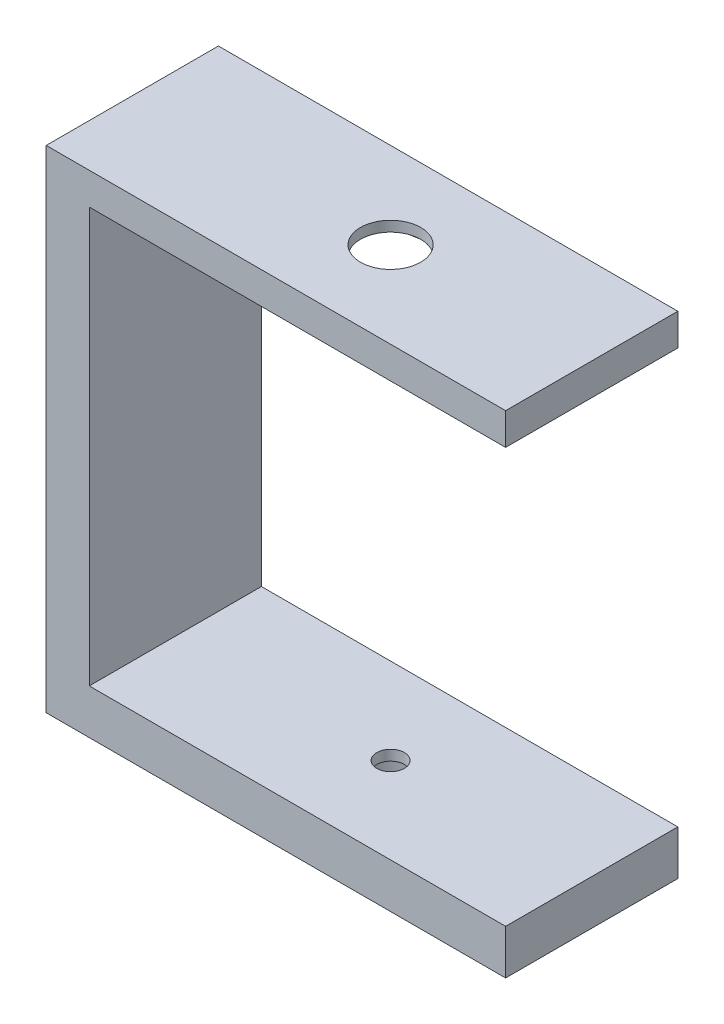
SolidWorks part; units mm, degrees
ref_plane "Alzado" through (0, 0, 0) normal (0, 0, 1) x (1, 0, 0)
ref_plane "Planta" through (0, 0, 0) normal (0, 1, 0) x (1, 0, 0)
ref_plane "Vista lateral" through (0, 0, 0) normal (1, 0, 0) x (0, 0, -1)
sketch "Croquis1" plane through (0, 0, 0) normal (0, 1, 0) x (1, 0, 0)
  line L1 (0, 0) -> (53.36, 0)
  line L2 (0, 0) -> (0, 20)
  line L3 (0, 20) -> (53.36, 20)
  line L4 (53.36, 0) -> (53.36, 20)
  dimension "D1" = 20
  dimension "D2" = 53.36
extrude "Saliente-Extruir1" add sketch "Croquis1" along normal blind 3.7
sketch "Croquis2" plane through (0, 0, 0) normal (0, -1, 0) x (1, 0, 0)
  line L0 (0, -20) -> (0, 0) construction
  line L1 (0, -20) -> (0, 0)
  line L2 (0, 0) -> (5, 0)
  line L3 (0, 0) -> (53.36, 0) construction
  line L4 (5, 0) -> (5, -20)
  line L5 (53.36, -20) -> (0, -20) construction
  line L6 (5, -20) -> (0, -20)
  dimension "D1" = 5
extrude "Saliente-Extruir2" add sketch "Croquis2" along normal blind 48.17
sketch "Croquis3" plane through (0, -48.17, 0) normal (0, -1, 0) x (1, 0, 0)
  line L0 (0, 0) -> (0, -20) construction
  line L1 (0, 0) -> (0, -20)
  line L2 (0, 0) -> (53.36, 0)
  line L3 (53.36, 0) -> (53.36, -20)
  line L4 (53.36, -20) -> (0, -20)
extrude "Saliente-Extruir3" add sketch "Croquis3" along normal blind 5.2
sketch "Croquis4" plane through (0, 0, 0) normal (0, -1, 0) x (1, 0, 0)
  line L0 (5, -10) -> (30, -10) construction
  line L1 (5, -20) -> (5, 0) construction
  line L2 (28.8973, -3.7465) -> (13.8394, -6.4016)
  line L3 (28.8973, -16.2535) -> (13.8394, -13.5984)
  line L4 (30, -3.65) -> (30, -16.35)
  arc A0 (28.8973, -16.2535) -> (30, -16.35) centre (30, -10) ccw
  arc A1 (13.8394, -13.5984) -> (13.8394, -6.4016) centre (14.4739, -10) cw
  arc A2 (30, -3.65) -> (28.8973, -3.7465) centre (30, -10) ccw
  point P10 (10.82, -10)
  dimension "D1" = 12.7
  dimension "D2" = 25
  dimension "D3" = 19.18
  dimension "D4" = 10
extrude "Cortar-Extruir1" cut sketch "Croquis4" against normal blind 2.5
mirror "Simetría1" about plane through (30, 2.5, -3.65) normal (1, 0, 0) of "Cortar-Extruir1"
sketch "Croquis5" plane through (0, 2.5, 0) normal (0, -1, 0) x (1, 0, 0)
  line L0 (30, -3.65) -> (30, -16.35) construction
  circle A0 centre (30, -10) radius 3.5
  arc A1 (31.1027, -3.7465) -> (28.8973, -3.7465) centre (30, -10) ccw construction
  arc A2 (28.8973, -16.2535) -> (31.1027, -16.2535) centre (30, -10) ccw construction
  point P11 (30, -10)
  dimension "D1" = 7
extrude "Cortar-Extruir2" cut sketch "Croquis5" against normal through all
ref_point "Punto1"
sketch "Croquis6" plane through (0, -53.37, 0) normal (0, -1, 0) x (1, 0, 0)
  circle A0 centre (30, -10) radius 5
  dimension "D1" = 10
extrude "Cortar-Extruir3" cut sketch "Croquis6" against normal blind 4
sketch "Croquis7" plane through (0, -49.37, 0) normal (0, -1, 0) x (1, 0, 0)
  circle A0 centre (30, -10) radius 1.6
  dimension "D1" = 3.2
extrude "Cortar-Extruir4" cut sketch "Croquis7" against normal through all
